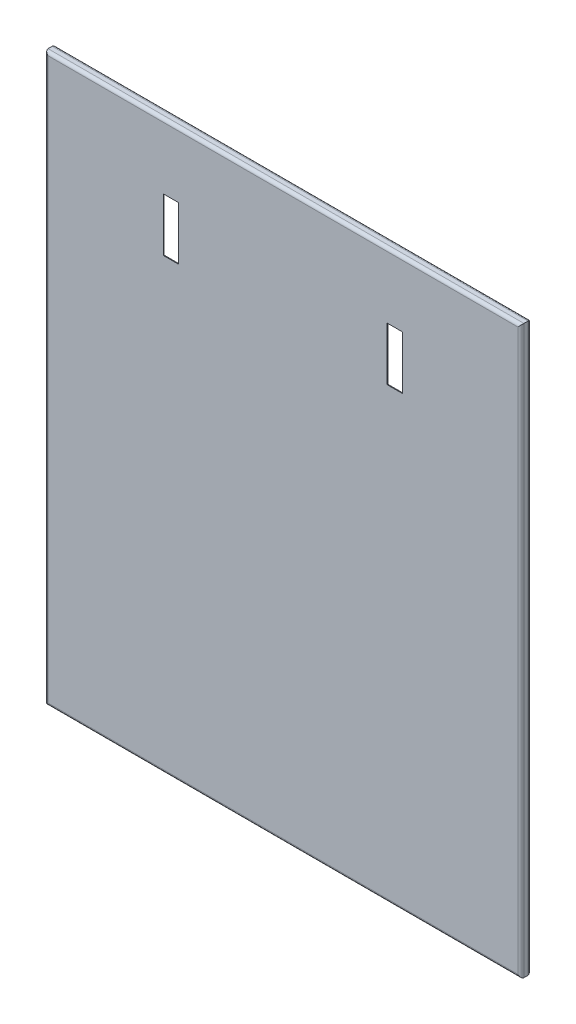
SolidWorks part; units mm, degrees
ref_plane "정면" through (0, 0, 0) normal (0, 0, 1) x (1, 0, 0)
ref_plane "윗면" through (0, 0, 0) normal (0, 1, 0) x (1, 0, 0)
ref_plane "우측면" through (0, 0, 0) normal (1, 0, 0) x (0, 0, -1)
sketch "스케치1" plane through (0, 0, 0) normal (0, 0, 1) x (1, 0, 0)
  line L1 (0, 0) -> (776, 0)
  line L2 (0, 0) -> (0, 924)
  line L3 (0, 924) -> (776, 924)
  line L4 (776, 0) -> (776, 924)
  line L5 (193, 818) -> (218, 818)
  line L6 (193, 818) -> (193, 731)
  line L7 (193, 731) -> (218, 731)
  line L8 (218, 818) -> (218, 731)
  line L9 (558, 818) -> (583, 818)
  line L10 (558, 818) -> (558, 731)
  line L11 (558, 731) -> (583, 731)
  line L12 (583, 818) -> (583, 731)
  point P14 (218, 774.5)
  dimension "D1" = 924
  dimension "D2" = 776
  dimension "D3" = 193
  dimension "D4" = 25
  dimension "D5" = 340
  dimension "D6" = 25
  dimension "D7" = 87
  dimension "D8" = 731
extrude "보스-돌출1" add sketch "스케치1" along normal blind 1.2
sketch "스케치2" plane through (0, 0, 0) normal (0, 0, -1) x (-1, 0, 0)
  line L0 (-1.2, 922.8) -> (-774.8, 922.8)
  line L1 (-774.8, 922.8) -> (-774.8, 1.2)
  line L2 (-774.8, 1.2) -> (-1.2, 1.2)
  line L3 (-1.2, 1.2) -> (-1.2, 922.8)
  line L4 (0, 0) -> (0, 924)
  line L5 (0, 924) -> (-776, 924)
  line L6 (-776, 924) -> (-776, 0)
  line L7 (-776, 0) -> (0, 0)
  line L8 (0, 0) -> (0, 924)
  line L9 (0, 924) -> (-776, 924)
  line L10 (-776, 924) -> (-776, 0)
  line L11 (-776, 0) -> (0, 0)
  dimension "D1" = 0
  dimension "D2" = 1.2
extrude "보스-돌출2" add sketch "스케치2" along normal blind 15.5
sketch "스케치3" plane through (0, 0, -15.5) normal (0, 0, -1) x (-1, 0, 0)
  line L0 (-15, 909) -> (-761, 909)
  line L1 (-761, 909) -> (-761, 15)
  line L2 (-761, 15) -> (-15, 15)
  line L3 (-15, 15) -> (-15, 909)
  line L4 (-776, 0) -> (0, 0)
  line L5 (0, 0) -> (0, 924)
  line L6 (0, 924) -> (-776, 924)
  line L7 (-776, 924) -> (-776, 0)
  line L8 (-776, 0) -> (0, 0)
  line L9 (0, 0) -> (0, 924)
  line L10 (0, 924) -> (-776, 924)
  line L11 (-776, 924) -> (-776, 0)
  dimension "D1" = 0
  dimension "D2" = 15
extrude "보스-돌출3" add sketch "스케치3" against normal blind 1.2
fillet "필렛1" radius 2 12 edges at (774.8, 462, 0) (774.8, 462, -14.3) (388, 1.2, 0) (388, 1.2, -14.3) (774.8, 1.2, -7.15) (1.2, 462, 0) (1.2, 462, -14.3) (1.2, 1.2, -7.15) (388, 922.8, 0) (774.8, 922.8, -7.15) (388, 922.8, -14.3) (1.2, 922.8, -7.15)
fillet "필렛2" radius 5 4 edges at (388, 924, 1.2) (388, 0, 1.2) (0, 462, 1.2) (776, 462, 1.2)
fillet "필렛3" radius 5 4 edges at (776, 462, -15.5) (388, 924, -15.5) (0, 462, -15.5) (388, 0, -15.5)
